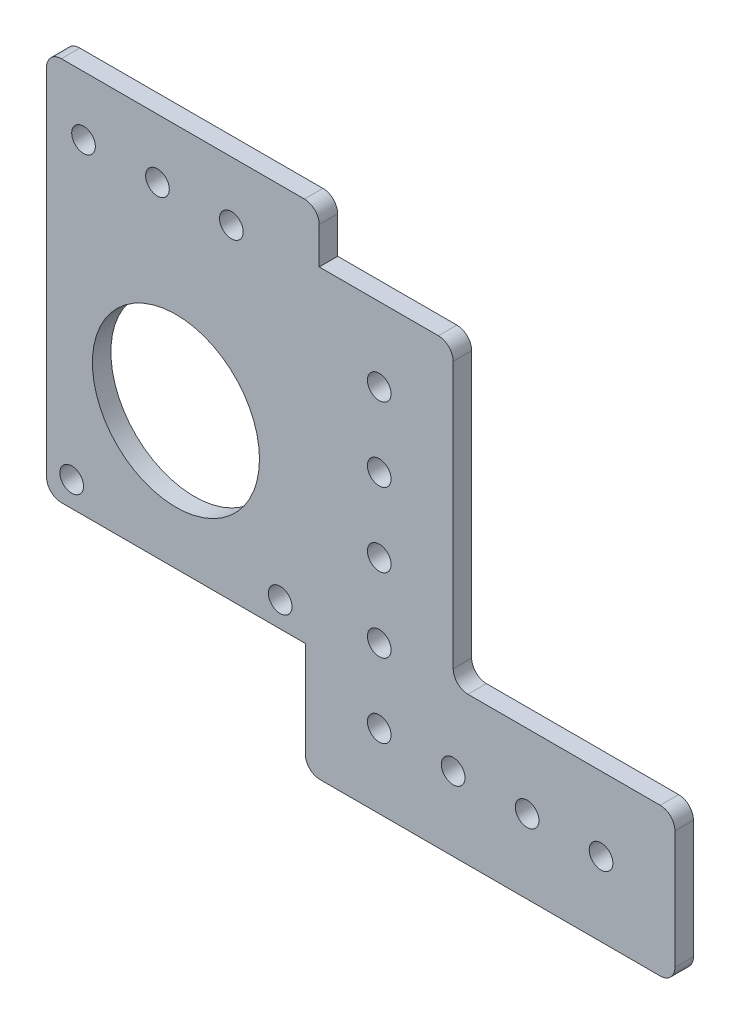
SolidWorks part; units mm, degrees
ref_plane "Front Plane" through (0, 0, 0) normal (0, 0, 1) x (1, 0, 0)
ref_plane "Top Plane" through (0, 0, 0) normal (0, 1, 0) x (1, 0, 0)
ref_plane "Right Plane" through (0, 0, 0) normal (1, 0, 0) x (0, 0, -1)
sketch "Sketch1" plane through (0, 0, 0) normal (0, 0, 1) x (1, 0, 0)
  line L0 (0, -38.1) -> (0, 38.1) construction
  line L1 (-12.7, -38.1) -> (12.7, -38.1)
  line L2 (-12.7, -38.1) -> (-12.7, 38.1)
  line L3 (-12.7, 38.1) -> (12.7, 38.1)
  line L4 (12.7, -38.1) -> (12.7, 38.1)
  line L5 (-12.7, -38.1) -> (12.7, 38.1) construction
  line L6 (-12.7, 38.1) -> (12.7, -38.1) construction
  line L7 (-34.925, 26.611) -> (-34.925, -17.839) construction
  line L8 (-55.88, -17.839) -> (-13.97, -17.839) construction
  line L9 (-12.7, 38.1) -> (-12.7, -38.1)
  line L10 (-55.88, -17.839) -> (-55.88, 26.611) construction
  line L11 (-55.88, 26.611) -> (-13.97, 26.611) construction
  line L12 (-12.7, -24.638) -> (-12.7, 24.638)
  line L13 (-13.97, -17.839) -> (-13.97, 26.611) construction
  line L14 (-55.88, -17.839) -> (-13.97, 26.611) construction
  line L15 (-55.88, 26.611) -> (-13.97, -17.839) construction
  line L16 (-57.15, -19.109) -> (-12.7, -19.109)
  line L17 (-57.15, -19.109) -> (-57.15, 27.881)
  line L18 (-57.15, 27.881) -> (-12.7, 27.881)
  line L19 (-12.7, -19.109) -> (-12.7, 27.881)
  line L20 (-57.15, -19.109) -> (-12.7, 27.881) construction
  line L21 (-57.15, 27.881) -> (-12.7, -19.109) construction
  circle A0 centre (-34.925, 4.386) radius 14.351
  circle A1 centre (-52.832, 23.563) radius 2.032 construction
  circle A2 centre (-17.018, -14.791) radius 2.032
  circle A3 centre (-52.832, -14.791) radius 2.032
  circle A4 centre (-17.018, 23.563) radius 2.032 construction
  point P0 (0, 0)
  point P6 (-34.925, 4.386)
  point P9 (0, 0)
  point P16 (-34.925, 4.386)
  dimension "D5" = 1.27
  dimension "D10" = 3.048
  dimension "D7" = 4.064
  dimension "D12" = 28.702
  dimension "D1" = 76.2
  dimension "D2" = 25.4
  dimension "D3" = 41.91
  dimension "D4" = 44.45
  dimension "D6" = 1.27
  dimension "D8" = 3.048
  dimension "D9" = 3.048
  dimension "D11" = 3.048
  dimension "D13" = 42.486
extrude "Boss-Extrude1" add sketch "Sketch1" along normal blind 3.175
sketch "Sketch2" plane through (0, 0, 3.175) normal (0, 0, 1) x (1, 0, 0)
  line L0 (0, 38.1) -> (0, -38.1) construction
  line L1 (-12.7, 38.1) -> (12.7, 38.1) construction
  line L2 (-12.7, -38.1) -> (12.7, -38.1) construction
  circle A0 centre (0, 0) radius 2.032
  circle A1 centre (0, 12.7) radius 2.032
  circle A2 centre (0, 25.4) radius 2.032
  circle A3 centre (0, -12.7) radius 2.032
  circle A4 centre (0, -25.4) radius 2.032
  dimension "D1" = 4.064
  dimension "D2" = 3
  dimension "D3" = 3
extrude "Cut-Extrude1" cut sketch "Sketch2" against normal through all
sketch "Sketch4" plane through (12.7, 0, 0) normal (1, 0, 0) x (0, 0, -1)
  line L0 (0, -38.1) -> (0, 38.1) construction
  line L1 (-3.175, -38.1) -> (0, -38.1)
  line L2 (-3.175, -38.1) -> (-3.175, -12.7)
  line L3 (-3.175, -12.7) -> (0, -12.7)
  line L4 (0, -38.1) -> (0, -12.7)
  dimension "D1" = 25.4
extrude "Boss-Extrude2" add sketch "Sketch4" along normal blind 38.1
sketch "Sketch5" plane through (0, 0, 0) normal (0, 0, -1) x (-1, 0, 0)
  circle A0 centre (0, -25.4) radius 2.032 construction
  circle A1 centre (0, -25.4) radius 2.032
  circle A2 centre (-12.7, -25.4) radius 2.032
  circle A3 centre (-25.4, -25.4) radius 2.032
  circle A4 centre (-38.1, -25.4) radius 2.032
  dimension "D1" = 4
extrude "Cut-Extrude2" cut sketch "Sketch5" against normal through all
fillet "Fillet5" radius 2.54 6 edges at (-12.7, -38.1, 1.5875) (-57.15, -19.109, 1.5875) (12.7, 38.1, 1.5875) (12.7, -12.7, 1.5875) (50.8, -12.7, 1.5875) (50.8, -38.1, 1.5875)
sketch "Sketch6" plane through (0, 0, 0) normal (0, 0, -1) x (-1, 0, 0)
  line L0 (10.3111, 46.931) -> (57.15, 46.931)
  line L1 (57.15, 27.881) -> (12.7, 27.881) construction
  line L2 (57.15, 46.931) -> (57.15, 27.881)
  line L4 (10.3111, 46.931) -> (10.3111, 27.881)
  line L5 (10.3111, 27.881) -> (57.15, 27.881)
  line L7 (57.15, -16.569) -> (57.15, 27.881) construction
  dimension "D1" = 19.05
extrude "Boss-Extrude3" add sketch "Sketch6" against normal up to surface (3.175 mm away) up to face at (10.668, -25.4, 3.175)
sketch "Sketch7" plane through (0, 0, 0) normal (0, 0, -1) x (-1, 0, 0)
  line L0 (57.15, 46.931) -> (10.3111, 46.931) construction
  line L1 (57.15, -16.569) -> (57.15, 46.931) construction
  circle A5 centre (12.7, 36.771) radius 2.032 construction
  circle A6 centre (25.4, 36.771) radius 2.032
  circle A7 centre (38.1, 36.771) radius 2.032
  circle A8 centre (50.8, 36.771) radius 2.032
  dimension "D1" = 10.16
  dimension "D2" = 6.35
extrude "Cut-Extrude3" cut sketch "Sketch7" against normal through all
fillet "Fillet6" radius 2.54 2 edges at (-10.3111, 46.931, 1.5875) (-57.15, 46.931, 1.5875)
